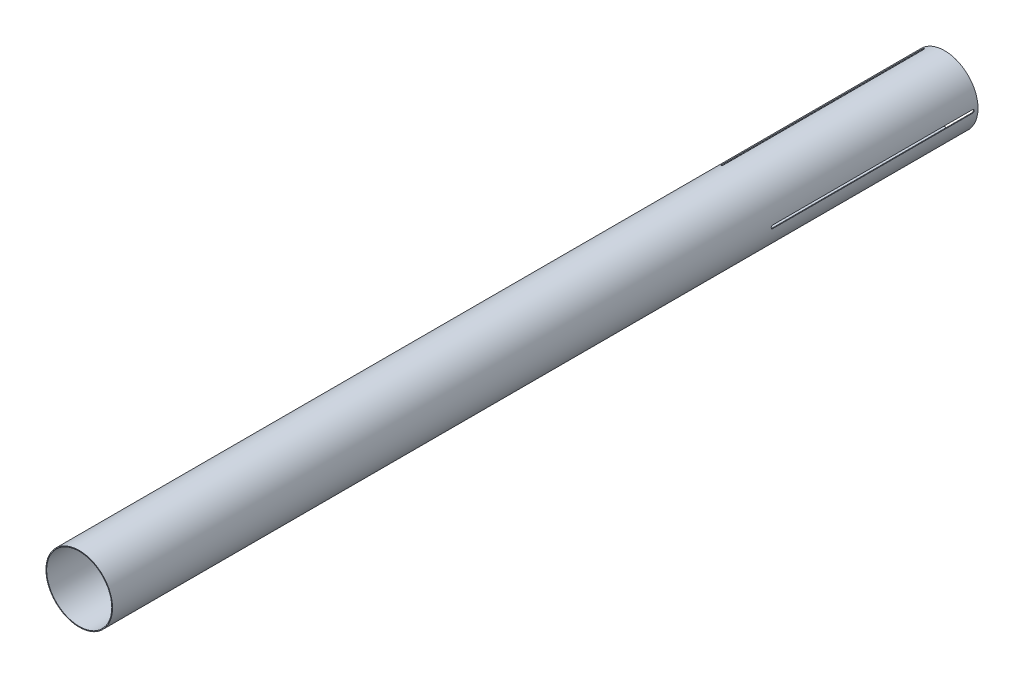
SolidWorks part; units mm, degrees
material "E-Glass Fiber"
ref_plane "Front Plane" through (0, 0, 0) normal (0, 0, 1) x (1, 0, 0)
ref_plane "Top Plane" through (0, 0, 0) normal (0, 1, 0) x (1, 0, 0)
ref_plane "Right Plane" through (0, 0, 0) normal (1, 0, 0) x (0, 0, -1)
sketch "Sketch1" plane through (0, 0, 0) normal (0, 0, 1) x (1, 0, 0)
  circle A0 centre (0, 0) radius 50.8
  circle A1 centre (0, 0) radius 49.6697
  dimension "D1" = 101.6
  dimension "D2" = 99.3394
extrude "Boss-Extrude1" add sketch "Sketch1" along normal blind 1320.8
ref_plane "Plane1" through (50.8, 0, 0) normal (1, 0, 0) x (0, 0, -1)
sketch "Sketch2" plane through (50.8, 0, 0) normal (1, 0, 0) x (0, 0, -1)
  line L0 (-8.382, 0) -> (-313.182, 0) construction
  line L1 (-8.382, -2.3812) -> (-313.182, -2.3813)
  line L2 (-8.382, 2.3813) -> (-313.182, 2.3812)
  line L3 (0, -50.8) -> (0, 50.8) construction
  arc A0 (-8.382, -2.3812) -> (-8.382, 2.3813) centre (-8.382, 0) ccw
  arc A1 (-313.182, 2.3812) -> (-313.182, -2.3813) centre (-313.182, 0) ccw
  point P3 (-160.782, 0)
  dimension "D1" = 4.7625
  dimension "D2" = 8.382
  dimension "D3" = 304.8
extrude "Cut-Extrude1" cut sketch "Sketch2" against normal up to next
pattern_circular "CirPattern1" count 3 over 360 about axis through (0, 0, 0) along (0, 0, 1) of "Cut-Extrude1"
